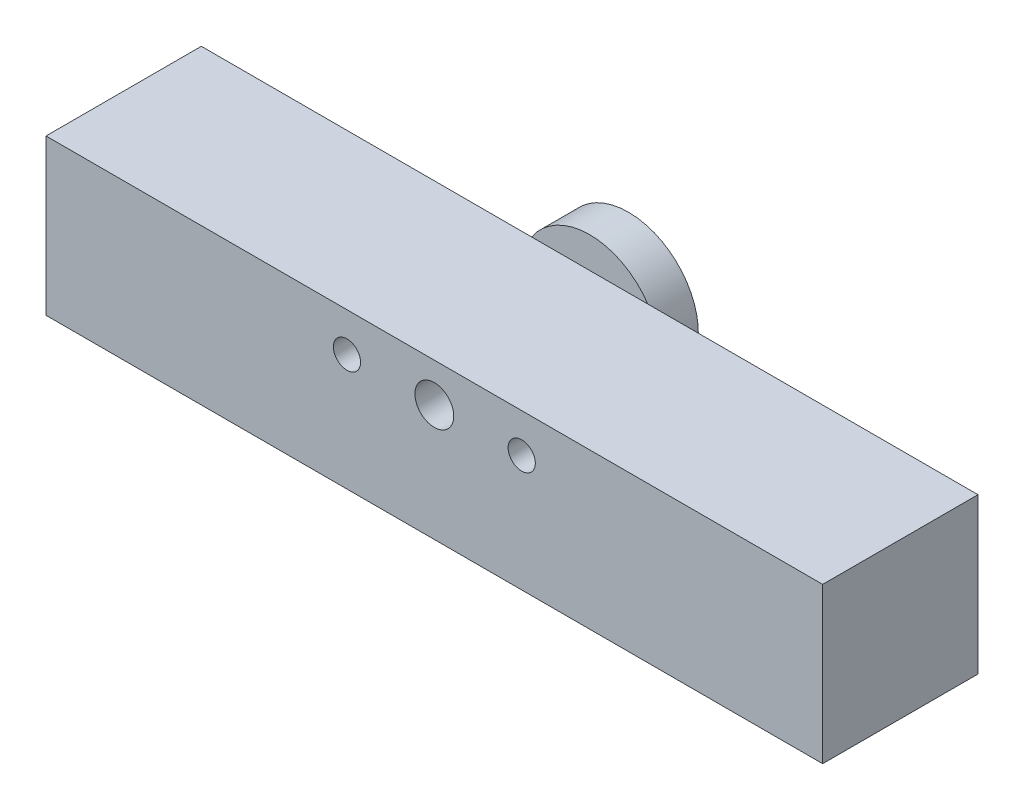
SolidWorks part; units mm, degrees
ref_plane "Front Plane" through (0, 0, 0) normal (0, 0, 1) x (1, 0, 0)
ref_plane "Top Plane" through (0, 0, 0) normal (0, 1, 0) x (1, 0, 0)
ref_plane "Right Plane" through (0, 0, 0) normal (1, 0, 0) x (0, 0, -1)
sketch "Sketch2" plane through (0, 0, 0) normal (0, 1, 0) x (1, 0, 0)
  line L1 (0, 0) -> (200, 0)
  line L2 (0, 0) -> (0, 40)
  line L3 (0, 40) -> (200, 40)
  line L4 (200, 0) -> (200, 40)
extrude "Boss-Extrude1" add sketch "Sketch2" along normal blind 40
sketch "Sketch3" plane through (0, 0, -40) normal (0, 0, -1) x (-1, 0, 0)
  circle A0 centre (-100, 30) radius 18
extrude "Boss-Extrude2" add sketch "Sketch3" along normal blind 10
sketch "Sketch4" plane through (0, 0, -50) normal (0, 0, -1) x (-1, 0, 0)
  circle A0 centre (-100, 30) radius 5
extrude "Cut-Extrude1" cut sketch "Sketch4" against normal blind 51
sketch "Sketch5" plane through (0, 0, -50) normal (0, 0, -1) x (-1, 0, 0)
  circle A0 centre (-77.5, 30) radius 3.5
  circle A1 centre (-122.5, 30) radius 3.5
extrude "Cut-Extrude2" cut sketch "Sketch5" against normal blind 51
